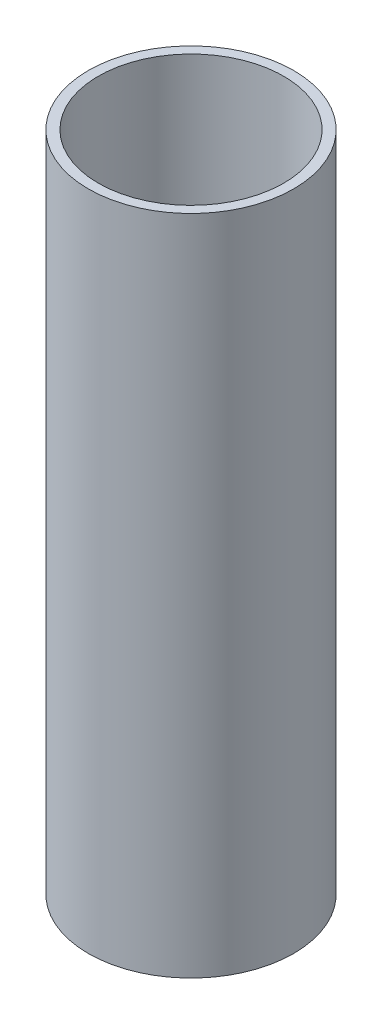
SolidWorks part; units mm, degrees
material "ABS PC"
ref_plane "Front Plane" through (0, 0, 0) normal (0, 0, 1) x (1, 0, 0)
ref_plane "Top Plane" through (0, 0, 0) normal (0, 1, 0) x (1, 0, 0)
ref_plane "Right Plane" through (0, 0, 0) normal (1, 0, 0) x (0, 0, -1)
sketch "Sketch1" plane through (0, 0, 0) normal (0, 1, 0) x (1, 0, 0)
  circle A0 centre (0, 0) radius 15.5
  circle A1 centre (0, 0) radius 14
  dimension "D1" = 31
  dimension "D2" = 28
extrude "Boss-Extrude1" add sketch "Sketch1" along normal mid plane 100
